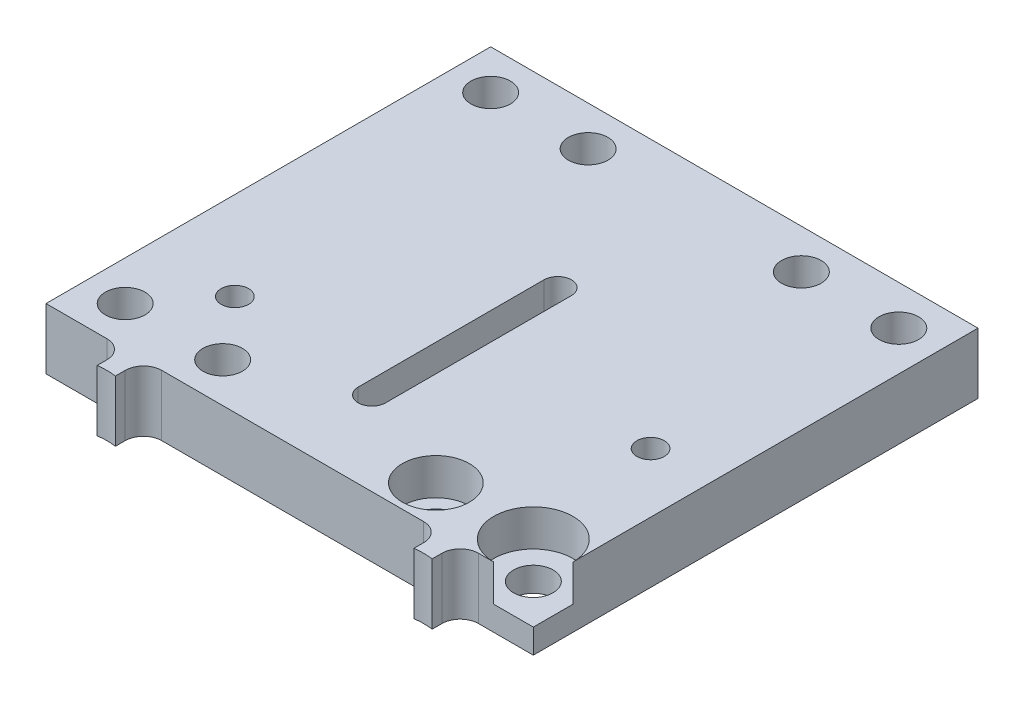
SolidWorks part; units mm, degrees
ref_plane "Front Plane" through (0, 0, 0) normal (0, 0, 1) x (1, 0, 0)
ref_plane "Top Plane" through (0, 0, 0) normal (0, 1, 0) x (1, 0, 0)
ref_plane "Right Plane" through (0, 0, 0) normal (1, 0, 0) x (0, 0, -1)
sketch "Sketch1" plane through (0, 0, 0) normal (0, 1, 0) x (1, 0, 0)
  line L1 (0, 0) -> (80, 0)
  line L2 (0, 0) -> (0, 73)
  line L3 (0, 73) -> (80, 73)
  line L4 (80, 0) -> (80, 73)
  dimension "D1" = 73
  dimension "D2" = 80
extrude "Boss-Extrude1" add sketch "Sketch1" along normal blind 10
sketch "Sketch3" plane through (0, 0, 0) normal (0, -1, 0) x (-1, 0, 0)
  line L0 (0, 6.5) -> (-80, 6.5) construction
  line L1 (0, 73) -> (0, 0) construction
  line L2 (-80, 0) -> (-80, 73) construction
  line L3 (0, 0) -> (-80, 0) construction
  line L4 (0, 36.5) -> (-12.8981, 36.5) construction
  circle A0 centre (-6.5, 6.5) radius 3.25
  circle A1 centre (-22.5, 6.5) radius 3.25
  circle A2 centre (-57.5, 6.5) radius 3.25
  circle A3 centre (-73.5, 6.5) radius 3.25
  circle A4 centre (-73.5, 66.5) radius 3.25
  circle A5 centre (-57.5, 66.5) radius 3.25
  circle A6 centre (-22.5, 66.5) radius 3.25
  circle A7 centre (-6.5, 66.5) radius 3.25
  dimension "D2" = 16
  dimension "D6" = 6.5
  dimension "D1" = 6.5
  dimension "D3" = 16
  dimension "D4" = 6.5
  dimension "D5" = 6.5
extrude "Cut-Extrude1" cut sketch "Sketch3" against normal blind 10
sketch "Sketch4" plane through (0, 10, 0) normal (0, 1, 0) x (1, 0, 0)
  line L0 (14, 73) -> (14, -14) construction
  line L1 (80, 73) -> (0, 73) construction
  line L2 (0, 73) -> (0, 0) construction
  line L3 (0, 0) -> (80, 0) construction
  line L4 (25.5, -14) -> (54.5, -14) construction
  line L5 (0, 0) -> (0, -30)
  line L6 (0, -30) -> (80, -30)
  line L7 (80, -30) -> (80, 0)
  line L8 (80, 0) -> (80, 73) construction
  line L9 (80, 0) -> (0, 0)
  circle A0 centre (14, -14) radius 11.5
  circle A1 centre (66, -14) radius 11.5
  dimension "D3" = 23
  dimension "D4" = 29
  dimension "D1" = 14
  dimension "D2" = 14
  dimension "D5" = 30
extrude "Boss-Extrude2" add sketch "Sketch4" against normal up to surface (10 mm away) up to face at (22.5, 0, -9.75)
sketch "Sketch5" plane through (0, 10, 0) normal (0, 1, 0) x (1, 0, 0)
  line L0 (0, -0.5) -> (80, -0.5)
  line L2 (0, 73) -> (0, -30) construction
  line L3 (80, -30) -> (80, 73) construction
  line L4 (0, -0.5) -> (0, -30)
  line L5 (0, -30) -> (80, -30)
  line L6 (80, -30) -> (80, -0.5)
  circle A1 centre (6.5, 6.5) radius 3.25 construction
  circle A2 centre (14, -14) radius 11.5
  circle A3 centre (66, -14) radius 11.5
  dimension "D1" = 7
extrude "Boss-Extrude3" add sketch "Sketch5" along normal blind 6
sketch "Sketch6" plane through (0, 10, 0) normal (0, 1, 0) x (1, 0, 0)
  line L0 (70.25, 44.25) -> (70.25, 13.75) construction
  line L3 (80, -0.5) -> (80, 73) construction
  line L4 (70.25, 29) -> (39.75, 29) construction
  line L5 (39.75, 13.75) -> (39.75, 44.25) construction
  line L6 (37.5, 13.75) -> (37.5, 44.25)
  line L7 (42, 13.75) -> (42, 44.25)
  line L8 (80, -0.5) -> (0, -0.5) construction
  arc A2 (37.5, 13.75) -> (42, 13.75) centre (39.75, 13.75) ccw
  arc A3 (42, 44.25) -> (37.5, 44.25) centre (39.75, 44.25) ccw
  circle A4 centre (70.25, 29) radius 2.25
  point P2 (70.25, 29)
  point P13 (39.75, 29)
  point P22 (39.75, 11.5)
  dimension "D3" = 2.25
  dimension "D6" = 12
extrude "Cut-Extrude2" cut sketch "Sketch6" against normal blind 28
sketch "Sketch7" plane through (0, 16, 0) normal (0, 1, 0) x (1, 0, 0)
  line L1 (0, 0) -> (80, 0)
  line L2 (0, 0) -> (0, -30)
  line L3 (0, -30) -> (80, -30)
  line L4 (80, 0) -> (80, -30)
extrude "Cut-Extrude3" cut sketch "Sketch7" against normal blind 20
sketch "Sketch8" plane through (0, 10, 0) normal (0, 1, 0) x (1, 0, 0)
  line L0 (6.5, 6.5) -> (22.5, 6.5) construction
  line L1 (22.5, 6.5) -> (14.5, 6.5) construction
  line L2 (14.5, 6.5) -> (14.5, -4.5) construction
  line L3 (13, -4.6028) -> (13, 0)
  line L4 (0, 0) -> (80, 0) construction
  line L5 (13, 0) -> (16, 0)
  line L6 (16, 0) -> (16, -4.6028)
  line L7 (40.5, 0) -> (40.5, -8.382) construction
  line L8 (65, 0) -> (65, -4.6028)
  line L9 (68, 0) -> (65, 0)
  line L10 (68, -4.6028) -> (68, 0)
  arc A0 (16, -4.6028) -> (13, -4.6028) centre (14.5, -15.5) ccw
  arc A1 (65, -4.6028) -> (68, -4.6028) centre (66.5, -15.5) cw
  dimension "D2" = 22
  dimension "D3" = 3
  dimension "D4" = 1.5
  dimension "D5" = 26
  dimension "D6" = 22
extrude "Boss-Extrude4" add sketch "Sketch8" against normal blind 10
sketch "Sketch9" plane through (0, 10, 0) normal (0, 1, 0) x (1, 0, 0)
  line L4 (73.5, 0) -> (80, 0)
  line L5 (80, 0) -> (80, 6.5)
  arc A3 (80, 6.5) -> (73.5, 0) centre (73.5, 6.5) ccw
  circle A7 centre (57.5, 6.5) radius 5.5
  point P1 (0, 0)
extrude "Cut-Extrude4" cut sketch "Sketch9" against normal blind 6
fillet "Fillet1" radius 3 4 edges at (68, 5, 0) (65, 5, 0) (16, 5, 0) (13, 5, 0)
sketch "Sketch10" plane through (0, 10, 0) normal (0, 1, 0) x (1, 0, 0)
  line L0 (22.5, 6.5) -> (6.5, 6.5) construction
  line L1 (6.5, 6.5) -> (14.5, 6.5) construction
  line L2 (14.5, 6.5) -> (14.5, 16.5) construction
  circle A0 centre (14.5, 16.5) radius 2.25
  dimension "D1" = 4.5
  dimension "D2" = 10
extrude "Cut-Extrude5" cut sketch "Sketch10" against normal blind 16
sketch "Sketch11" plane through (0, 0, 0) normal (0, -1, 0) x (-1, 0, 0)
  line L1 (-10.4585, 16.5) -> (-12.4793, 20)
  line L2 (-12.4793, 20) -> (-16.5207, 20)
  line L3 (-16.5207, 20) -> (-18.5415, 16.5)
  line L4 (-18.5415, 16.5) -> (-16.5207, 13)
  line L5 (-16.5207, 13) -> (-12.4793, 13)
  line L6 (-12.4793, 13) -> (-10.4585, 16.5)
  circle A0 centre (-14.5, 16.5) radius 3.5 construction
  dimension "D1" = 7
extrude "Cut-Extrude6" cut sketch "Sketch11" against normal blind 6
